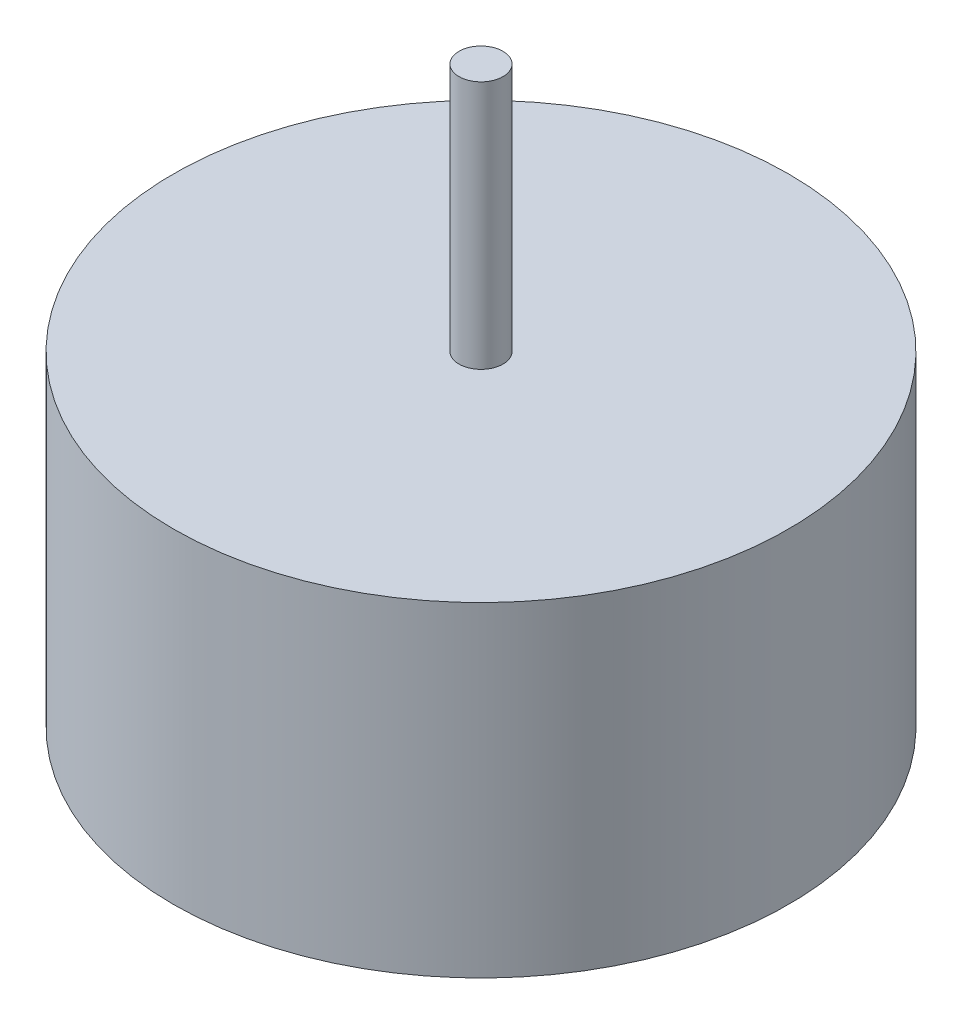
SolidWorks part; units mm, degrees
ref_plane "Front Plane" through (0, 0, 0) normal (0, 0, 1) x (1, 0, 0)
ref_plane "Top Plane" through (0, 0, 0) normal (0, 1, 0) x (1, 0, 0)
ref_plane "Right Plane" through (0, 0, 0) normal (1, 0, 0) x (0, 0, -1)
sketch "Sketch1" plane through (0, 0, 0) normal (0, 1, 0) x (1, 0, 0)
  circle A0 centre (0, 0) radius 21
extrude "Boss-Extrude1" add sketch "Sketch1" along normal blind 22.2
sketch "Sketch2" plane through (0, 0, 0) normal (0, 1, 0) x (1, 0, 0)
  circle A0 centre (0, 0) radius 1.5
extrude "Boss-Extrude2" add sketch "Sketch2" along normal blind 39.2
